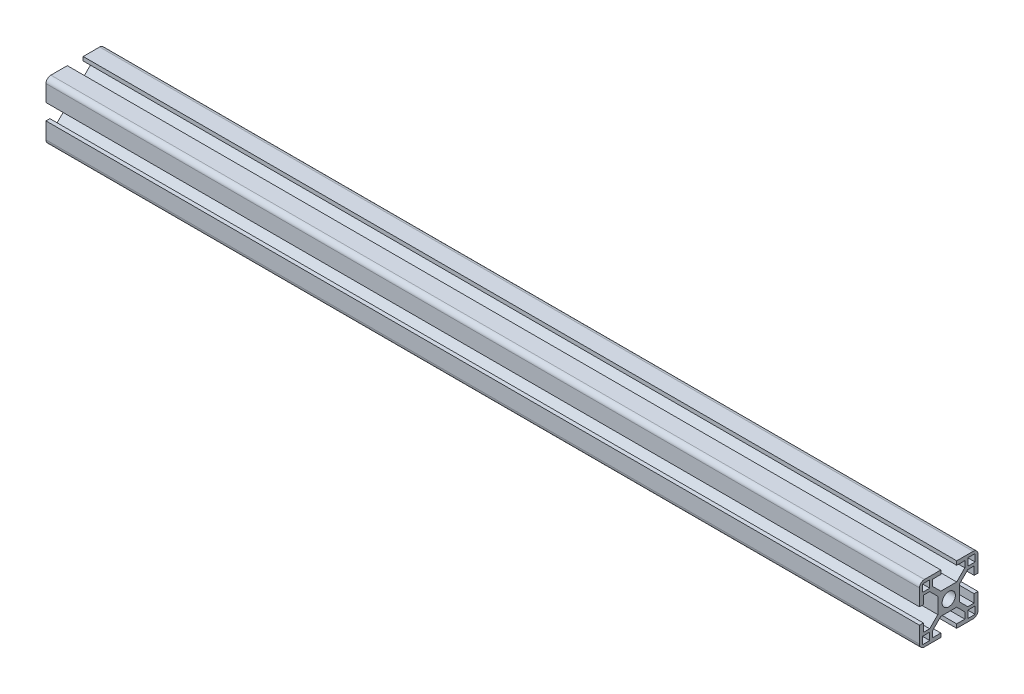
SolidWorks part; units mm, degrees
material "6061 Alloy"
ref_plane "Front Plane" through (0, 0, 0) normal (0, 0, 1) x (1, 0, 0)
ref_plane "Top Plane" through (0, 0, 0) normal (0, 1, 0) x (1, 0, 0)
ref_plane "Right Plane" through (0, 0, 0) normal (1, 0, 0) x (0, 0, -1)
sketch "Sketch1" plane through (0, 0, 0) normal (0, 1, 0) x (1, 0, 0)
  line L0 (0, 0) -> (448, 0)
  dimension "D1" = 448
other "T-slot profiles 3030_2(1)"
ref_plane "Plane1" through (0, 0, 0) normal (1, 0, 0) x (0, 0, -1)
sketch "Sketch13" plane through (0, 0, 0) normal (1, 0, 0) x (0, 0, -1)
  line L0 (0, 15) -> (0, -15) construction
  line L1 (-15, -15) -> (15, -15) construction
  line L2 (-15, -15) -> (-15, 15) construction
  line L3 (-15, 15) -> (15, 15) construction
  line L4 (15, -15) -> (15, 15) construction
  line L5 (-15, -15) -> (15, 15) construction
  line L6 (-15, 15) -> (15, -15) construction
  line L7 (-4.07, 5.6) -> (4.07, 5.6)
  line L8 (0, 0) -> (15, 0) construction
  line L9 (-4.07, -5.6) -> (4.07, -5.6)
  line L10 (5.6, -4.07) -> (5.6, 4.07)
  line L11 (-5.6, -4.07) -> (-5.6, 4.07)
  line L12 (-4.07, 5.6) -> (-8.25, 9.78)
  line L13 (4.07, 5.6) -> (8.25, 9.78)
  line L14 (-8.25, 9.78) -> (8.25, 9.78) construction
  line L15 (8.25, 9.78) -> (8.25, 13)
  line L16 (8.25, 13) -> (4.07, 13)
  line L17 (4.07, 13) -> (4.07, 15)
  line L18 (4.07, 15) -> (12.5, 15)
  line L19 (15, 12.5) -> (15, 4.07)
  line L20 (9.78, 8.25) -> (13, 8.25)
  line L21 (13, 8.25) -> (13, 4.07)
  line L22 (9.78, 8.25) -> (5.6, 4.07)
  line L23 (8.25, 9.78) -> (9.78, 8.25) construction
  line L24 (13, 4.07) -> (15, 4.07)
  line L25 (5.6, -4.07) -> (9.78, -8.25)
  line L26 (9.75, 13.5) -> (13.5, 13.5)
  line L27 (9.75, 13.5) -> (9.75, 9.75)
  line L28 (9.75, 9.75) -> (13.5, 9.75)
  line L29 (13.5, 13.5) -> (13.5, 9.75)
  line L30 (9.75, 13.5) -> (13.5, 9.75) construction
  line L31 (9.75, 9.75) -> (13.5, 13.5) construction
  line L32 (9.78, -8.25) -> (13, -8.25)
  line L33 (13, -8.25) -> (13, -4.07)
  line L34 (13, -4.07) -> (15, -4.07)
  line L35 (15, -4.07) -> (15, -12.5)
  line L36 (4.07, -5.6) -> (8.25, -9.78)
  line L37 (8.25, -9.78) -> (8.25, -13)
  line L38 (8.25, -13) -> (4.07, -13)
  line L39 (4.07, -13) -> (4.07, -15)
  line L40 (4.07, -15) -> (12.5, -15)
  line L41 (-4.07, -5.6) -> (-8.25, -9.78)
  line L42 (-8.25, -9.78) -> (-8.25, -13)
  line L43 (-8.25, -13) -> (-4.07, -13)
  line L44 (-4.07, -13) -> (-4.07, -15)
  line L45 (-4.07, -15) -> (-12.5, -15)
  line L46 (-8.25, 9.78) -> (-8.25, 13)
  line L47 (-8.25, 13) -> (-4.07, 13)
  line L48 (-4.07, 13) -> (-4.07, 15)
  line L49 (-4.07, 15) -> (-12.5, 15)
  line L50 (-5.6, 4.07) -> (-9.78, 8.25)
  line L51 (-9.78, 8.25) -> (-13, 8.25)
  line L52 (-13, 8.25) -> (-13, 4.07)
  line L53 (-13, 4.07) -> (-15, 4.07)
  line L54 (-15, 4.07) -> (-15, 12.5)
  line L55 (-5.6, -4.07) -> (-9.78, -8.25)
  line L56 (-9.78, -8.25) -> (-13, -8.25)
  line L57 (-13, -8.25) -> (-13, -4.07)
  line L58 (-13, -4.07) -> (-15, -4.07)
  line L59 (-15, -4.07) -> (-15, -12.5)
  line L60 (9.75, -9.75) -> (13.5, -9.75)
  line L61 (13.5, -13.5) -> (13.5, -9.75)
  line L62 (9.75, -13.5) -> (13.5, -13.5)
  line L63 (9.75, -13.5) -> (9.75, -9.75)
  line L64 (-9.75, 9.75) -> (-13.5, 9.75)
  line L65 (-13.5, 13.5) -> (-13.5, 9.75)
  line L66 (-9.75, 13.5) -> (-13.5, 13.5)
  line L67 (-9.75, 13.5) -> (-9.75, 9.75)
  line L68 (-9.75, -13.5) -> (-9.75, -9.75)
  line L69 (-9.75, -13.5) -> (-13.5, -13.5)
  line L70 (-13.5, -13.5) -> (-13.5, -9.75)
  line L71 (-9.75, -9.75) -> (-13.5, -9.75)
  arc A0 (-15, 12.5) -> (-12.5, 15) centre (-12.5, 12.5) cw
  arc A1 (12.5, -15) -> (15, -12.5) centre (12.5, -12.5) ccw
  arc A2 (15, 12.5) -> (12.5, 15) centre (12.5, 12.5) ccw
  arc A3 (-12.5, -15) -> (-15, -12.5) centre (-12.5, -12.5) cw
  circle A4 centre (0, 0) radius 3.4
  point P0 (0, 0)
  point P6 (0, 0)
  point P7 (-12.5, 12.5)
  point P26 (0, 5.6)
  point P32 (5.6, 0)
  point P44 (11.625, 11.625)
  dimension "D4" = 6.8
  dimension "D3" = 2.5
  dimension "D1" = 30
  dimension "D2" = 30
  dimension "D5" = 8.14
  dimension "D6" = 9.4
  dimension "D7" = 8.14
  dimension "D8" = 9.4
  dimension "D9" = 16.5
  dimension "D10" = 2
  dimension "D11" = 2
  dimension "D12" = 3.75
  dimension "D13" = 3.75
  dimension "D14" = 1.5
  dimension "D15" = 2
  dimension "D16" = 2
  dimension "D17" = 2
  dimension "D18" = 2
  dimension "D19" = 2
  dimension "D20" = 2
